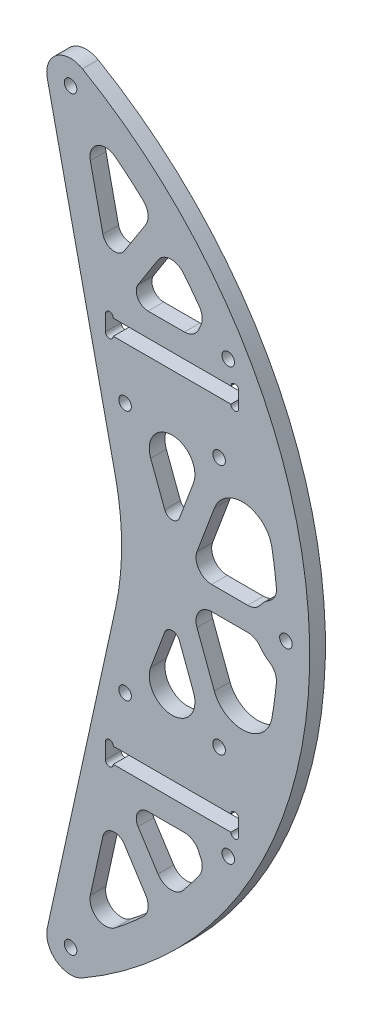
SolidWorks part; units mm, degrees
material "6061 Alloy"
ref_plane "Front" through (0, 0, 0) normal (0, 0, 1) x (1, 0, 0)
ref_plane "Top" through (0, 0, 0) normal (0, 1, 0) x (1, 0, 0)
ref_plane "Right" through (0, 0, 0) normal (1, 0, 0) x (0, 0, -1)
sketch "Sketch1" plane through (0, 0, 0) normal (0, 0, 1) x (1, 0, 0)
  line L6 (181.6436, 23.1269) -> (154.0241, 149.054)
  line L7 (154.0241, -149.054) -> (181.6436, -23.1269)
  arc A0 (181.6436, -23.1269) -> (181.6436, 23.1269) centre (76.2, 0) ccw
  arc A1 (-29.1028, -44.45) -> (-29.1028, 44.45) centre (76.2, 0) ccw construction
  arc A2 (168.275, -159.4786) -> (168.275, 159.4786) centre (76.2, 0) ccw
  arc A3 (-86.0278, -87.1399) -> (-15.875, -159.4786) centre (76.2, 0) ccw construction
  circle A4 centre (163.45, 151.1214) radius 3.9624 construction
  circle A5 centre (163.45, 151.1214) radius 3.9624 construction
  circle A6 centre (163.45, -151.1214) radius 3.9624 construction
  circle A7 centre (163.45, -151.1214) radius 3.9624 construction
  circle A8 centre (76.2, 0) radius 101.6 construction
  arc A9 (168.275, 159.4786) -> (154.0241, 149.054) centre (163.45, 151.1214) ccw
  arc A10 (154.0241, -149.054) -> (168.275, -159.4786) centre (163.45, -151.1214) ccw
  dimension "D3" = 203.2
  dimension "D4" = 6.35
extrude "Boss-Extrude1" add sketch "Sketch1" along normal blind 6.35 contours L7 A0 L6 A9 A2 A10
hole_wizard "#10 Clearance Hole1" positions "Sketch2" profile "Sketch3" hole size "#10" standard "ANSI Inch" end condition through all
sketch "Sketch2" plane through (0, 0, 0) normal (0, 0, -1) x (-1, 0, 0)
  circle A0 centre (-227.3214, -87.25) radius 3.9624 construction
  circle A1 centre (-250.7, 0) radius 3.9624 construction
  circle A2 centre (-227.3214, 87.25) radius 3.9624 construction
  circle A3 centre (-163.45, -151.1214) radius 3.9624 construction
  circle A4 centre (-163.45, 151.1214) radius 3.9624 construction
  point P0 (-227.3214, 87.25)
  point P3 (-250.7, 0)
  point P6 (-227.3214, -87.25)
  point P18 (-163.45, 151.1214)
  point P20 (-163.45, -151.1214)
sketch "Sketch3" plane through (227.3214, 87.25, 0) normal (1, 0, 0) x (0, 1, 0)
  line L0 (0, 0) -> (0, 6.35)
  line L1 (0, 6.35) -> (2.5527, 6.35)
  line L2 (2.5527, 6.35) -> (2.5527, 0)
  line L5 (2.5527, 0) -> (0, 0)
  line L11 (0, -6.35) -> (0, 107.95) construction
  dimension "Thru Hole Dia." = 5.1054
  dimension "Thru Hole Depth" = 6.35
sketch "Sketch4" plane through (0, 0, 0) normal (0, 0, -1) x (-1, 0, 0)
  line L0 (-231.5646, -78.2605) -> (-231.5646, -71.9105) construction
  line L1 (-228.3896, -71.9105) -> (-180.7646, -71.9105)
  line L2 (-231.5646, -71.9105) -> (-231.5646, -78.2605)
  line L3 (-228.3896, -78.2605) -> (-180.7646, -78.2605)
  line L4 (-177.5896, -71.9105) -> (-177.5896, -78.2605)
  line L5 (-228.3896, 78.2605) -> (-180.7646, 78.2605)
  line L6 (-231.5646, 78.2605) -> (-231.5646, 71.9105)
  line L7 (-228.3896, 71.9105) -> (-180.7646, 71.9105)
  line L8 (-177.5896, 78.2605) -> (-177.5896, 71.9105)
  line L9 (-177.5896, -78.2605) -> (-177.5896, -71.9105) construction
  line L10 (-222.0396, -78.2605) -> (-231.5646, -78.2605) construction
  line L11 (-222.0396, -71.9105) -> (-231.5646, -71.9105) construction
  line L12 (-231.5646, 71.9105) -> (-231.5646, 78.2605) construction
  line L13 (-177.5896, 71.9105) -> (-177.5896, 78.2605) construction
  line L14 (-218.8646, 78.2605) -> (-177.5896, 78.2605) construction
  line L16 (-222.0396, 71.9105) -> (-231.5646, 71.9105) construction
  arc A0 (-228.3896, 78.2605) -> (-231.5646, 78.2605) centre (-229.9771, 78.2605) ccw
  arc A1 (-177.5896, 78.2605) -> (-180.7646, 78.2605) centre (-179.1771, 78.2605) ccw
  arc A2 (-231.5646, 71.9105) -> (-228.3896, 71.9105) centre (-229.9771, 71.9105) ccw
  arc A3 (-180.7646, 71.9105) -> (-177.5896, 71.9105) centre (-179.1771, 71.9105) ccw
  arc A4 (-177.5896, -71.9105) -> (-180.7646, -71.9105) centre (-179.1771, -71.9105) ccw
  arc A5 (-180.7646, -78.2605) -> (-177.5896, -78.2605) centre (-179.1771, -78.2605) ccw
  arc A6 (-231.5646, -78.2605) -> (-228.3896, -78.2605) centre (-229.9771, -78.2605) ccw
  arc A7 (-228.3896, -71.9105) -> (-231.5646, -71.9105) centre (-229.9771, -71.9105) ccw
  dimension "D1" = 3.175
extrude "Cut-Extrude3" cut sketch "Sketch4" against normal through all
hole_wizard "#10 Clearance Hole2" positions "Sketch5" profile "Sketch6" hole size "#10" standard "ANSI Inch" end condition through all
sketch "Sketch5" plane through (0, 0, 0) normal (0, 0, -1) x (-1, 0, 0)
  point P0 (-223.6271, -50.8)
  point P2 (-185.5271, 50.8)
  point P4 (-185.5271, -50.8)
  point P6 (-223.6271, 50.8)
sketch "Sketch6" plane through (223.6271, -50.8, 0) normal (1, 0, 0) x (0, 1, 0)
  line L0 (0, 0) -> (0, 6.35)
  line L1 (0, 6.35) -> (2.5527, 6.35)
  line L2 (2.5527, 6.35) -> (2.5527, 0)
  line L5 (2.5527, 0) -> (0, 0)
  line L11 (0, -6.35) -> (0, 107.95) construction
  dimension "Thru Hole Dia." = 5.1054
  dimension "Thru Hole Depth" = 6.35
sketch "Sketch7" plane through (0, 0, 6.35) normal (0, 0, 1) x (1, 0, 0)
  line L0 (171.448, 128.8924) -> (176.5578, 105.595)
  line L1 (194.8231, 87.7855) -> (209.5593, 87.7855)
  line L2 (185.2206, 104.0474) -> (193.8789, 117.5709)
  line L3 (185.5271, 50.8) -> (223.6271, -50.8) construction
  line L4 (181.6436, 23.1269) -> (154.0241, 149.054) construction
  line L5 (180.7646, 78.2605) -> (228.3896, 78.2605) construction
  line L6 (223.6271, 50.8) -> (185.5271, -50.8) construction
  line L7 (195.9183, 36.6537) -> (201.6042, 21.4912)
  line L8 (196.1367, 36.0711) -> (187.2182, 32.7267) construction
  line L9 (204.5771, 0) -> (250.7, 0) construction
  line L10 (213.2359, 36.6537) -> (207.5499, 21.4912)
  line L11 (221.695, 32.0843) -> (214.6667, 13.3421)
  line L12 (209.8054, 27.5059) -> (218.724, 24.1614) construction
  line L13 (198.8625, 107.6897) -> (190.8122, 95.1159)
  line L14 (199.4907, 0) -> (185.2017, -38.1042) construction
  line L15 (199.4907, 0) -> (185.2017, 38.1042) construction
  line L16 (235.227, 4.7625) -> (220.6124, 4.7625)
  line L17 (200.1199, 118.4861) -> (180.4639, 87.7855) construction
  line L18 (192.0325, 114.687) -> (200.0543, 109.5512) construction
  line L19 (235.227, -4.7625) -> (220.6124, -4.7625)
  line L20 (221.695, -32.0843) -> (214.6667, -13.3421)
  line L21 (213.2359, -36.6537) -> (207.5499, -21.4912)
  line L22 (195.9183, -36.6537) -> (201.6042, -21.4912)
  line L23 (194.8231, -87.7855) -> (209.5593, -87.7855)
  line L24 (198.8625, -107.6897) -> (190.8122, -95.1159)
  line L25 (185.2206, -104.0474) -> (193.8789, -117.5709)
  line L26 (171.448, -128.8924) -> (176.5578, -105.595)
  circle A0 centre (163.45, 151.1214) radius 12.7 construction
  arc A1 (216.0743, 93.1484) -> (215.48, 91.8403) centre (227.3214, 87.25) ccw
  circle A2 centre (223.6271, 50.8) radius 12.7 construction
  circle A3 centre (185.5271, 50.8) radius 12.7 construction
  arc A4 (181.5525, 135.2625) -> (171.448, 128.8924) centre (177.6505, 130.2528) ccw
  circle A5 centre (185.5271, -50.8) radius 12.7 construction
  circle A6 centre (223.6271, -50.8) radius 12.7 construction
  arc A7 (243.9089, 10.7318) -> (240.3846, 7.4083) centre (250.7, 0) ccw
  arc A8 (181.5525, 135.2625) -> (192.8515, 125.6484) centre (76.2, 0) cw
  arc A9 (168.275, -159.4786) -> (168.275, 159.4786) centre (76.2, 0) ccw construction
  arc A10 (245.0153, 29.9418) -> (221.695, 32.0843) centre (233.0619, 27.8217) ccw
  arc A13 (201.6042, 21.4912) -> (207.5499, 21.4912) centre (204.5771, 22.606) ccw
  arc A14 (213.2359, 36.6537) -> (195.9183, 36.6537) centre (204.5771, 39.9007) ccw
  arc A15 (245.0153, 29.9418) -> (246.8331, 16.7168) centre (76.2, 0) cw
  arc A16 (240.3846, 7.4083) -> (235.227, 4.7625) centre (235.227, 11.1125) cw
  arc A17 (246.8331, 16.7168) -> (243.9089, 10.7318) centre (240.5133, 16.0977) cw
  arc A18 (220.6124, 4.7625) -> (214.6667, 13.3421) centre (220.6124, 11.1125) cw
  arc A19 (209.1338, 108.276) -> (215.6142, 99.7937) centre (76.2, 0) cw
  arc A20 (198.8625, 107.6897) -> (209.1338, 108.276) centre (204.2103, 104.2658) cw
  arc A21 (193.8789, 117.5709) -> (192.8515, 125.6484) centre (188.5311, 120.9948) ccw
  arc A22 (176.5578, 105.595) -> (185.2206, 104.0474) centre (181.2097, 106.6154) ccw
  arc A23 (194.8231, 87.7855) -> (190.8122, 95.1159) centre (194.8231, 92.548) cw
  arc A24 (209.5593, 87.7855) -> (215.48, 91.8403) centre (209.5593, 94.1355) ccw
  arc A25 (216.0743, 93.1484) -> (215.6142, 99.7937) centre (210.4507, 96.0977) ccw
  arc A26 (240.3846, -7.4083) -> (235.227, -4.7625) centre (235.227, -11.1125) ccw
  arc A27 (243.9089, -10.7318) -> (240.3846, -7.4083) centre (250.7, 0) cw
  arc A28 (246.8331, -16.7168) -> (243.9089, -10.7318) centre (240.5133, -16.0977) ccw
  arc A29 (245.0153, -29.9418) -> (246.8331, -16.7168) centre (76.2, 0) ccw
  arc A30 (245.0153, -29.9418) -> (221.695, -32.0843) centre (233.0619, -27.8217) cw
  arc A31 (220.6124, -4.7625) -> (214.6667, -13.3421) centre (220.6124, -11.1125) ccw
  arc A32 (201.6042, -21.4912) -> (207.5499, -21.4912) centre (204.5771, -22.606) cw
  arc A33 (213.2359, -36.6537) -> (195.9183, -36.6537) centre (204.5771, -39.9007) cw
  arc A34 (209.5593, -87.7855) -> (215.48, -91.8403) centre (209.5593, -94.1355) cw
  arc A35 (216.0743, -93.1484) -> (215.48, -91.8403) centre (227.3214, -87.25) cw
  arc A36 (216.0743, -93.1484) -> (215.6142, -99.7937) centre (210.4507, -96.0977) cw
  arc A37 (209.1338, -108.276) -> (215.6142, -99.7937) centre (76.2, 0) ccw
  arc A38 (198.8625, -107.6897) -> (209.1338, -108.276) centre (204.2103, -104.2658) ccw
  arc A39 (194.8231, -87.7855) -> (190.8122, -95.1159) centre (194.8231, -92.548) ccw
  arc A40 (176.5578, -105.595) -> (185.2206, -104.0474) centre (181.2097, -106.6154) cw
  arc A41 (193.8789, -117.5709) -> (192.8515, -125.6484) centre (188.5311, -120.9948) cw
  arc A42 (181.5525, -135.2625) -> (192.8515, -125.6484) centre (76.2, 0) ccw
  arc A43 (181.5525, -135.2625) -> (171.448, -128.8924) centre (177.6505, -130.2528) cw
  point P46 (191.6775, 34.3989)
  point P53 (214.2647, 25.8337)
  point P69 (196.0434, 112.1191)
  point P73 (203.4678, 114.8826)
  dimension "D1" = 25.4
  dimension "D2" = 12.7
  dimension "D5" = 12.7
  dimension "D7" = 3.175
  dimension "D9" = 6.35
  dimension "D10" = 6.35
  dimension "D13" = 6.35
  dimension "D14" = 4.7625
  dimension "D15" = 6.35
  dimension "D3" = 9.525
  dimension "D4" = 12.7
  dimension "D6" = 9.525
  dimension "D8" = 9.525
  dimension "D11" = 9.525
  dimension "D12" = 45
extrude "Cut-Extrude4" cut sketch "Sketch7" against normal through all
